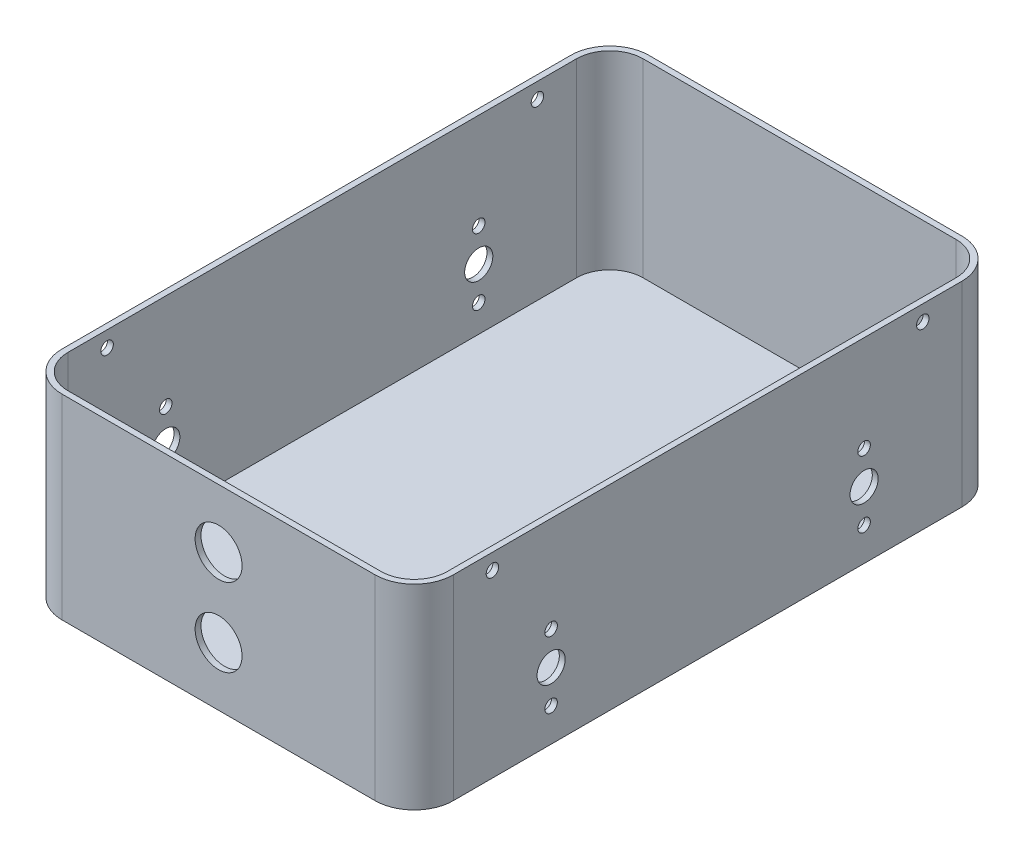
SolidWorks part; units mm, degrees
material "聚脂樹脂"
ref_plane "前视基准面" through (0, 0, 0) normal (0, 0, 1) x (1, 0, 0)
ref_plane "上视基准面" through (0, 0, 0) normal (0, 1, 0) x (1, 0, 0)
ref_plane "右视基准面" through (0, 0, 0) normal (1, 0, 0) x (0, 0, -1)
other "Configuration Table"
sketch "草圖3" plane through (0, 0, 0) normal (0, 1, 0) x (1, 0, 0)
  line L1 (10, 41.5531) -> (90, 41.5531)
  line L2 (0, 31.5531) -> (0, -98.4469)
  line L3 (10, -108.4469) -> (90, -108.4469)
  line L4 (100, 31.5531) -> (100, -98.4469)
  arc A0 (0, -98.4469) -> (10, -108.4469) centre (10, -98.4469) ccw
  arc A1 (90, -108.4469) -> (100, -98.4469) centre (90, -98.4469) ccw
  arc A2 (90, 41.5531) -> (100, 31.5531) centre (90, 31.5531) cw
  arc A3 (10, 41.5531) -> (0, 31.5531) centre (10, 31.5531) ccw
  dimension "D1" = 10
  dimension "D2" = 100
extrude "填料-伸長1" add sketch "草圖3" along normal blind 50 contours L2 A0 L3 A1 L4 A2 L1 A3
sketch "草圖4" plane through (0, 0, 0) normal (-1, 0, 0) x (0, 0, 1)
  line L0 (-31.5531, 50) -> (-31.5531, 0) construction
  line L1 (98.4469, 50) -> (98.4469, 0) construction
  line L2 (-6.5523, -10.7518) -> (-6.5523, 54.6884)
  line L3 (-6.5523, 25.5) -> (73.4477, 25.5) construction
  circle A0 centre (-6.5531, 17) radius 3.6
  circle A1 centre (73.4469, 17) radius 3.6
  circle A2 centre (-6.5531, 17) radius 12.5
  circle A5 centre (73.4469, 17) radius 12.5
  circle A7 centre (-6.5523, 25.5) radius 1.6
  circle A8 centre (-6.5523, 8.5) radius 1.6
  circle A9 centre (73.4477, 25.5) radius 1.6
  circle A10 centre (73.4477, 8.5) radius 1.6
  point P6 (73.4469, 17)
  dimension "D1" = 2
  dimension "D5" = 2
  dimension "D4" = 8.5
  dimension "D2" = 130
  dimension "D3" = 25
  dimension "D7" = 80
  dimension "D6" = 2
shell "薄殼1" thickness 1.5
extrude "除料-伸長1" cut sketch "草圖4" against normal through all and the other way through all contours A8 | A0 | A7 | A10 | A1 | A9
sketch "草圖6" plane through (0, 0, 108.4469) normal (0, 0, 1) x (1, 0, 0)
  line L0 (10, 50) -> (10, 0) construction
  line L1 (90, 50) -> (90, 0) construction
  line L2 (10, 50) -> (90, 50) construction
  circle A0 centre (50, 35) radius 6
  circle A2 centre (50, 15) radius 6
  dimension "D2" = 40
  dimension "D4" = 12
  dimension "D5" = 2
  dimension "D1" = 80
  dimension "D3" = 15
extrude "除料-伸長2" cut sketch "草圖6" against normal up to next
sketch "草圖7" plane through (100, 0, 0) normal (1, 0, 0) x (0, 0, -1)
  line L3 (31.5531, 50) -> (-98.4469, 50) construction
  circle A0 centre (-88.4469, 46) radius 1.6
  circle A1 centre (21.5531, 46) radius 1.6
  point P0 (-33.4469, 48.5993)
  point P7 (-88.8352, 47.2001)
  dimension "D1" = 55
  dimension "D2" = 4
extrude "除料-伸長3" cut sketch "草圖7" against normal through all
